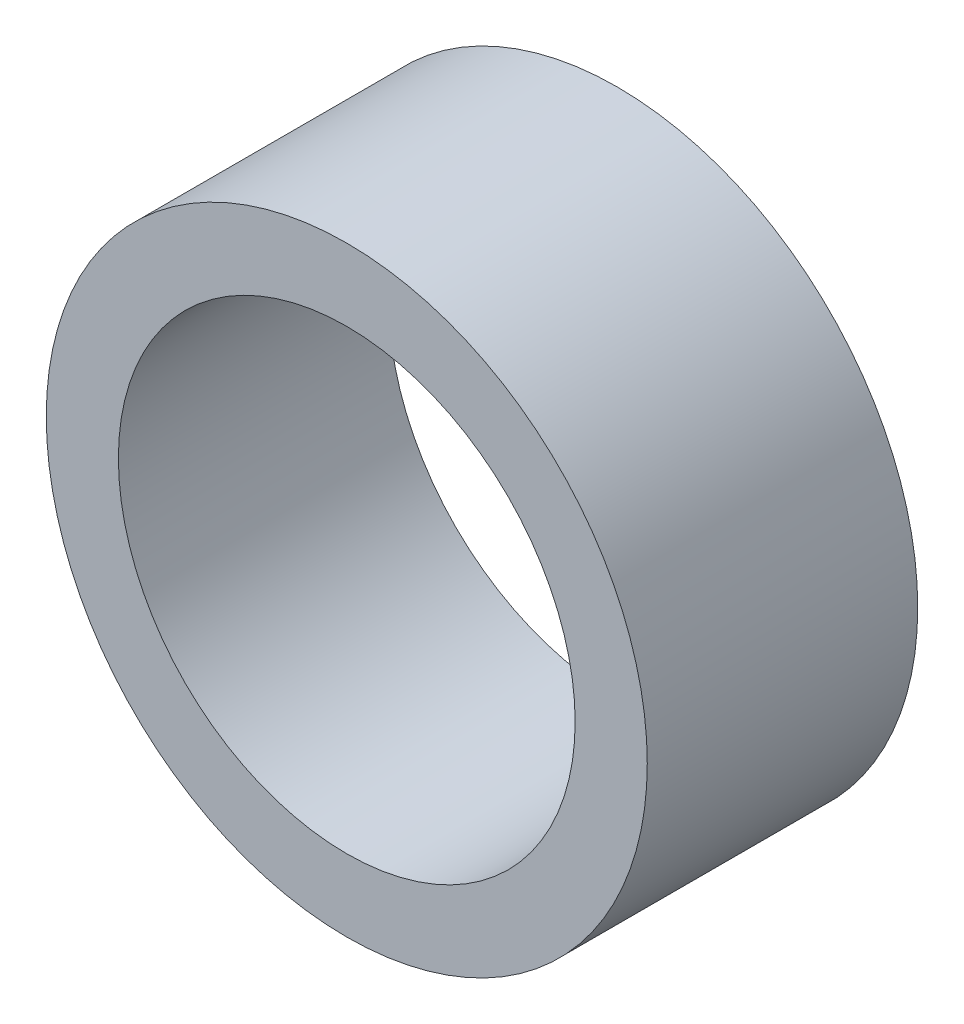
SolidWorks part; units mm, degrees
ref_plane "Front Plane" through (0, 0, 0) normal (0, 0, 1) x (1, 0, 0)
ref_plane "Top Plane" through (0, 0, 0) normal (0, 1, 0) x (1, 0, 0)
ref_plane "Right Plane" through (0, 0, 0) normal (1, 0, 0) x (0, 0, -1)
sketch "Sketch1" plane through (0, 0, 0) normal (0, 0, 1) x (1, 0, 0)
  circle A0 centre (0, 0) radius 7.6
  circle A1 centre (0, 0) radius 10
  dimension "D1" = 15.2
  dimension "D2" = 20
extrude "Boss-Extrude1" add sketch "Sketch1" along normal mid plane 9
